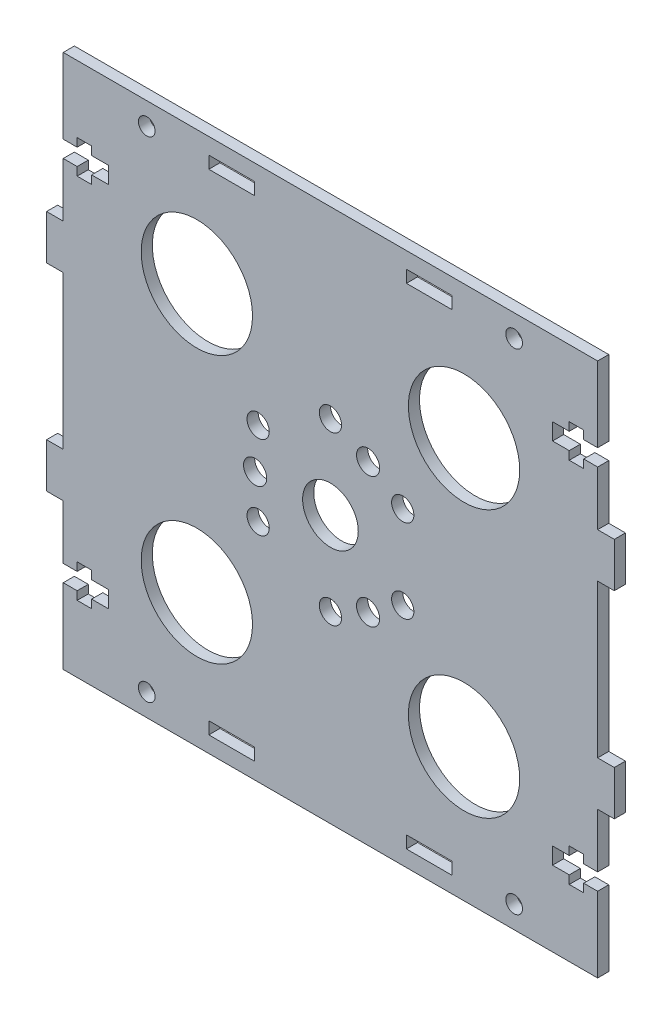
SolidWorks part; units mm, degrees
ref_plane "前视基准面" through (0, 0, 0) normal (0, 0, 1) x (1, 0, 0)
ref_plane "上视基准面" through (0, 0, 0) normal (0, 1, 0) x (1, 0, 0)
ref_plane "右视基准面" through (0, 0, 0) normal (1, 0, 0) x (0, 0, -1)
sketch "草图1" plane through (0, 0, 0) normal (0, 0, 1) x (1, 0, 0)
  line L1 (-24.1162, -115.6745) -> (-15.9162, -115.6745)
  line L2 (-15.9162, -113.4745) -> (-15.9162, -115.6745)
  line L3 (-24.1162, -113.4745) -> (-15.9162, -113.4745)
  line L4 (-24.1162, -113.4745) -> (-24.1162, -115.6745)
  line L5 (19.5838, -113.4745) -> (19.5838, -115.6745)
  line L6 (19.5838, -113.4745) -> (11.3838, -113.4745)
  line L7 (11.3838, -113.4745) -> (11.3838, -115.6745)
  line L10 (19.5838, -115.6745) -> (11.3838, -115.6745)
  line L38 (-35.2662, -114.5745) -> (-24.1162, -114.5745) construction
  line L60 (11.3838, -114.5745) -> (-15.9162, -114.5745) construction
  line L66 (19.5838, -114.5745) -> (30.7338, -114.5745) construction
  line L133 (-2.2662, -70.5745) -> (-2.2662, -75.5745) construction
  line L142 (-50.2662, -92.3245) -> (-50.2662, -102.0745)
  line L143 (45.7338, -23.5745) -> (45.7338, -22.5745)
  line L144 (45.7338, -106.0745) -> (45.7338, -118.5745)
  line L145 (-47.7662, -105.0745) -> (-47.7662, -106.5745)
  line L146 (19.5838, -25.4745) -> (11.3838, -25.4745)
  line L147 (11.3838, -27.6745) -> (11.3838, -25.4745)
  line L148 (19.5838, -27.6745) -> (11.3838, -27.6745)
  line L149 (19.5838, -27.6745) -> (19.5838, -25.4745)
  line L150 (-24.1162, -27.6745) -> (-24.1162, -25.4745)
  line L151 (-24.1162, -27.6745) -> (-15.9162, -27.6745)
  line L152 (-15.9162, -27.6745) -> (-15.9162, -25.4745)
  line L153 (-24.1162, -25.4745) -> (-15.9162, -25.4745)
  line L155 (-2.2662, -22.5745) -> (-50.2662, -22.5745)
  line L156 (30.7338, -26.5745) -> (19.5838, -26.5745) construction
  line L157 (-15.9162, -26.5745) -> (11.3838, -26.5745) construction
  line L158 (-24.1162, -26.5745) -> (-35.2662, -26.5745) construction
  line L159 (-47.7662, -102.0745) -> (-47.7662, -100.5745)
  line L170 (45.7338, -56.8245) -> (45.7338, -84.3245)
  line L171 (45.7338, -106.0745) -> (45.7338, -105.0745)
  line L172 (48.7338, -48.8245) -> (48.7338, -56.8245)
  line L173 (-50.2662, -102.0745) -> (-47.7662, -102.0745)
  line L174 (-47.7662, -106.5745) -> (-45.1662, -106.5745)
  line L175 (-45.1662, -106.5745) -> (-45.1662, -105.0745)
  line L176 (-45.1662, -105.0745) -> (-42.1662, -105.0745)
  line L177 (-42.1662, -102.0745) -> (-42.1662, -105.0745)
  line L178 (-45.1662, -102.0745) -> (-42.1662, -102.0745)
  line L179 (-45.1662, -100.5745) -> (-45.1662, -102.0745)
  line L180 (-47.7662, -100.5745) -> (-45.1662, -100.5745)
  line L181 (-47.7662, -105.0745) -> (-50.2662, -105.0745)
  line L182 (-50.2662, -39.0745) -> (-50.2662, -48.8245)
  line L183 (-47.7662, -40.5745) -> (-45.1662, -40.5745)
  line L184 (-47.7662, -36.0745) -> (-50.2662, -36.0745)
  line L185 (-45.1662, -40.5745) -> (-45.1662, -39.0745)
  line L186 (-45.1662, -39.0745) -> (-42.1662, -39.0745)
  line L187 (-42.1662, -39.0745) -> (-42.1662, -36.0745)
  line L188 (-45.1662, -36.0745) -> (-42.1662, -36.0745)
  line L189 (-45.1662, -34.5745) -> (-45.1662, -36.0745)
  line L190 (-47.7662, -34.5745) -> (-45.1662, -34.5745)
  line L191 (-50.2662, -39.0745) -> (-47.7662, -39.0745)
  line L192 (-47.7662, -39.0745) -> (-47.7662, -40.5745)
  line L193 (-47.7662, -36.0745) -> (-47.7662, -34.5745)
  line L194 (-50.2662, -36.0745) -> (-50.2662, -23.5745)
  line L195 (-50.2662, -48.8245) -> (-53.2662, -48.8245)
  line L196 (-53.2662, -56.8245) -> (-50.2662, -56.8245)
  line L197 (-53.2662, -92.3245) -> (-53.2662, -84.3245)
  line L198 (-50.2662, -84.3245) -> (-53.2662, -84.3245)
  line L199 (-53.2662, -92.3245) -> (-50.2662, -92.3245)
  line L200 (-53.2662, -48.8245) -> (-53.2662, -56.8245)
  line L201 (-50.2662, -106.0745) -> (-50.2662, -105.0745)
  line L202 (48.7338, -92.3245) -> (45.7338, -92.3245)
  line L203 (45.7338, -84.3245) -> (48.7338, -84.3245)
  line L204 (-50.2662, -56.8245) -> (-50.2662, -84.3245)
  line L205 (-50.2662, -106.0745) -> (-50.2662, -118.5745)
  line L206 (-50.2662, -23.5745) -> (-50.2662, -22.5745)
  line L207 (-47.3662, -48.7245) -> (-47.3662, -56.9245) [skipped]
  line L208 (-45.1662, -56.9245) -> (-47.3662, -56.9245) [skipped]
  line L209 (-45.1662, -48.7245) -> (-45.1662, -56.9245) [skipped]
  line L210 (-45.1662, -48.7245) -> (-47.3662, -48.7245) [skipped]
  line L211 (-45.1662, -92.4245) -> (-47.3662, -92.4245) [skipped]
  line L212 (-45.1662, -92.4245) -> (-45.1662, -84.2245) [skipped]
  line L213 (-45.1662, -84.2245) -> (-47.3662, -84.2245) [skipped]
  line L214 (-47.3662, -92.4245) -> (-47.3662, -84.2245) [skipped]
  line L217 (-46.2662, -37.5745) -> (-46.2662, -48.7245) construction
  line L218 (-46.2662, -84.2245) -> (-46.2662, -56.9245) construction
  line L219 (-46.2662, -92.4245) -> (-46.2662, -103.5745) construction
  line L221 (42.8338, -92.4245) -> (42.8338, -84.2245) [skipped]
  line L222 (40.6338, -84.2245) -> (42.8338, -84.2245) [skipped]
  line L223 (40.6338, -92.4245) -> (40.6338, -84.2245) [skipped]
  line L224 (40.6338, -92.4245) -> (42.8338, -92.4245) [skipped]
  line L225 (40.6338, -48.7245) -> (42.8338, -48.7245) [skipped]
  line L226 (40.6338, -48.7245) -> (40.6338, -56.9245) [skipped]
  line L227 (40.6338, -56.9245) -> (42.8338, -56.9245) [skipped]
  line L228 (42.8338, -48.7245) -> (42.8338, -56.9245) [skipped]
  line L230 (41.7338, -103.5745) -> (41.7338, -92.4245) construction
  line L231 (41.7338, -56.9245) -> (41.7338, -84.2245) construction
  line L232 (41.7338, -48.7245) -> (41.7338, -37.5745) construction
  line L233 (48.7338, -92.3245) -> (48.7338, -84.3245)
  line L234 (48.7338, -56.8245) -> (45.7338, -56.8245)
  line L235 (45.7338, -48.8245) -> (48.7338, -48.8245)
  line L236 (45.7338, -36.0745) -> (45.7338, -23.5745)
  line L237 (43.2338, -36.0745) -> (43.2338, -34.5745)
  line L238 (43.2338, -39.0745) -> (43.2338, -40.5745)
  line L239 (45.7338, -39.0745) -> (43.2338, -39.0745)
  line L240 (43.2338, -34.5745) -> (40.6338, -34.5745)
  line L241 (40.6338, -34.5745) -> (40.6338, -36.0745)
  line L242 (40.6338, -36.0745) -> (37.6338, -36.0745)
  line L243 (37.6338, -39.0745) -> (37.6338, -36.0745)
  line L244 (40.6338, -39.0745) -> (37.6338, -39.0745)
  line L245 (40.6338, -40.5745) -> (40.6338, -39.0745)
  line L246 (43.2338, -36.0745) -> (45.7338, -36.0745)
  line L247 (43.2338, -40.5745) -> (40.6338, -40.5745)
  line L248 (45.7338, -39.0745) -> (45.7338, -48.8245)
  line L249 (43.2338, -105.0745) -> (45.7338, -105.0745)
  line L250 (43.2338, -100.5745) -> (40.6338, -100.5745)
  line L251 (40.6338, -100.5745) -> (40.6338, -102.0745)
  line L252 (40.6338, -102.0745) -> (37.6338, -102.0745)
  line L253 (37.6338, -102.0745) -> (37.6338, -105.0745)
  line L254 (40.6338, -105.0745) -> (37.6338, -105.0745)
  line L255 (40.6338, -106.5745) -> (40.6338, -105.0745)
  line L256 (43.2338, -106.5745) -> (40.6338, -106.5745)
  line L257 (45.7338, -102.0745) -> (43.2338, -102.0745)
  line L258 (43.2338, -102.0745) -> (43.2338, -100.5745)
  line L259 (43.2338, -105.0745) -> (43.2338, -106.5745)
  line L260 (45.7338, -92.3245) -> (45.7338, -102.0745)
  line L261 (-2.2662, -22.5745) -> (45.7338, -22.5745)
  line L262 (45.7338, -118.5745) -> (-2.2662, -118.5745)
  line L263 (-2.2662, -118.5745) -> (-50.2662, -118.5745)
  circle A0 centre (-35.2662, -114.5745) radius 1.5
  circle A1 centre (30.7338, -114.5745) radius 1.5
  circle A11 centre (30.7338, -26.5745) radius 1.5
  circle A12 centre (-35.2662, -26.5745) radius 1.5
  circle A15 centre (-2.2662, -70.5745) radius 15 construction
  circle A16 centre (-2.2662, -70.5745) radius 13.53 construction
  circle A17 centre (-2.2662, -85.5717) radius 2
  circle A18 centre (-15.2541, -78.0731) radius 2
  circle A19 centre (-15.2541, -63.0759) radius 2
  circle A20 centre (-2.2662, -55.5773) radius 2
  circle A21 centre (10.7218, -63.0759) radius 2
  circle A22 centre (10.7218, -78.0731) radius 2
  circle A23 centre (-15.7962, -70.5745) radius 2.08
  circle A24 centre (4.4988, -58.8572) radius 2.08
  circle A25 centre (4.4988, -82.2918) radius 2.08
  circle A26 centre (-2.2662, -70.5745) radius 5
  circle A27 centre (-26.2662, -46.5745) radius 10
  circle A28 centre (21.7338, -46.5745) radius 10
  circle A29 centre (21.7338, -94.5745) radius 10
  circle A30 centre (-26.2662, -94.5745) radius 10
  circle A32 centre (-46.2662, -37.5745) radius 1.5 [skipped]
  circle A33 centre (-46.2662, -103.5745) radius 1.5 [skipped]
  circle A34 centre (41.7338, -103.5745) radius 1.5 [skipped]
  circle A35 centre (41.7338, -37.5745) radius 1.5 [skipped]
  point P116 (-41.6662, -37.0745)
  point P134 (37.1338, -103.0745)
  point P135 (37.1338, -37.0745)
  point P138 (-41.6662, -103.0745)
  dimension "D1" = 4
  dimension "D2" = 6
extrude "凸台-拉伸1" add sketch "草图1" along normal blind 2
